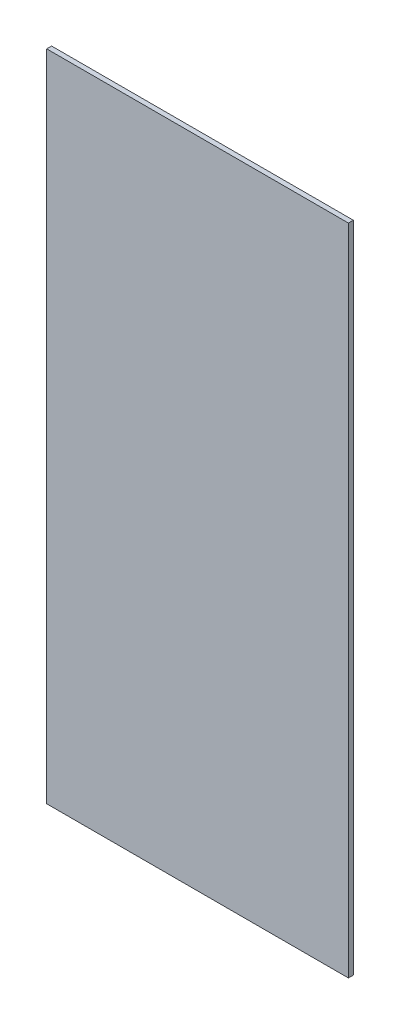
SolidWorks part; units mm, degrees
ref_plane "Спереди" through (0, 0, 0) normal (0, 0, 1) x (1, 0, 0)
ref_plane "Сверху" through (0, 0, 0) normal (0, 1, 0) x (1, 0, 0)
ref_plane "Справа" through (0, 0, 0) normal (1, 0, 0) x (0, 0, -1)
sketch "Эскиз1" plane through (0, 0, 0) normal (0, 1, 0) x (1, 0, 0)
  line L1 (0, 0) -> (245.9852, 0)
  line L2 (0, 0) -> (0, -4)
  line L3 (0, -4) -> (245.9852, -4)
  line L4 (245.9852, 0) -> (245.9852, -4)
extrude "Вытянуть1" add sketch "Эскиз1" along normal blind 533
